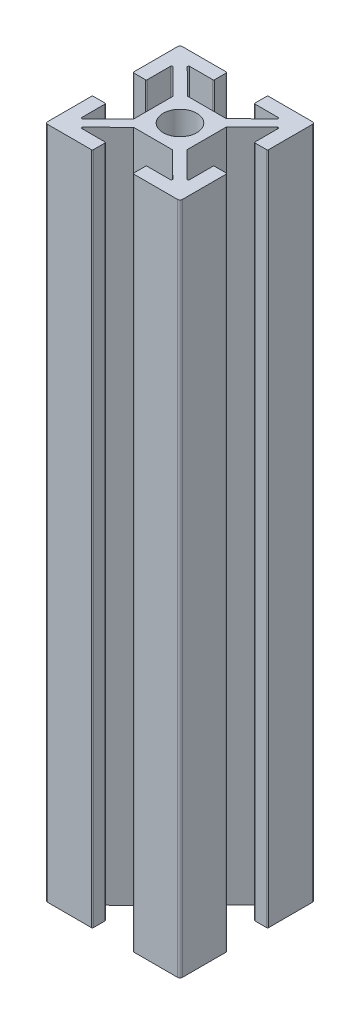
SolidWorks part; units mm, degrees
ref_plane "Front Plane" through (0, 0, 0) normal (0, 0, 1) x (1, 0, 0)
ref_plane "Top Plane" through (0, 0, 0) normal (0, 1, 0) x (1, 0, 0)
ref_plane "Right Plane" through (0, 0, 0) normal (1, 0, 0) x (0, 0, -1)
sketch "Sketch1" plane through (0, 0, 0) normal (0, 1, 0) x (1, 0, 0)
  line L0 (-5.3577, -5.6795) -> (-3.6577, -5.6795)
  line L1 (1.3423, 1.3205) -> (-5.1577, 1.3205)
  line L2 (-5.5077, -5.5295) -> (-5.5077, 0.9705)
  line L3 (7.3792, -4.6795) -> (1.6054, -4.6795)
  line L4 (0.5386, -11.6249) -> (0.5386, -5.7341)
  line L5 (-3.5077, -5.5295) -> (-3.5077, -2.0933)
  line L6 (-2.0758, -0.6795) -> (1.3423, -0.6795)
  line L7 (1.4923, -0.5295) -> (1.4923, 1.1705)
  line L8 (-3.5077, -0.6795) -> (0.5386, -4.6795) construction
  line L9 (-3.2523, -1.9866) -> (0.5386, -5.7341)
  line L10 (-2.1813, -0.9362) -> (1.6054, -4.6795)
  line L11 (12.4923, -0.6795) -> (8.446, -4.6795) construction
  line L12 (4.4923, -8.6795) -> (4.4923, 3.0091) construction
  line L13 (4.4923, -8.6795) -> (-10.4455, -8.6795) construction
  line L14 (11.1658, -0.9362) -> (7.3792, -4.6795)
  line L15 (12.2368, -1.9866) -> (8.446, -5.7341)
  line L16 (7.4923, -0.5295) -> (7.4923, 1.1705)
  line L17 (11.0604, -0.6795) -> (7.6423, -0.6795)
  line L18 (12.4923, -5.5295) -> (12.4923, -2.0933)
  line L19 (8.446, -11.6249) -> (8.446, -5.7341)
  line L20 (14.4923, -5.5295) -> (14.4923, 0.9705)
  line L21 (7.6423, 1.3205) -> (14.1423, 1.3205)
  line L22 (14.3423, -5.6795) -> (12.6423, -5.6795)
  line L23 (12.4923, -16.6795) -> (8.446, -12.6795) construction
  line L24 (-3.5077, -16.6795) -> (0.5386, -12.6795) construction
  line L25 (14.3423, -11.6795) -> (12.6423, -11.6795)
  line L26 (7.6423, -18.6795) -> (14.1423, -18.6795)
  line L27 (14.4923, -11.8295) -> (14.4923, -18.3295)
  line L28 (12.4923, -11.8295) -> (12.4923, -15.2657)
  line L29 (11.0604, -16.6795) -> (7.6423, -16.6795)
  line L30 (7.4923, -16.8295) -> (7.4923, -18.5295)
  line L31 (12.2368, -15.3723) -> (8.446, -11.6249)
  line L32 (11.1658, -16.4228) -> (7.3792, -12.6795)
  line L33 (-2.1813, -16.4228) -> (1.6054, -12.6795)
  line L34 (-3.2523, -15.3723) -> (0.5386, -11.6249)
  line L35 (1.4923, -16.8295) -> (1.4923, -18.5295)
  line L36 (-2.0758, -16.6795) -> (1.3423, -16.6795)
  line L37 (-3.5077, -11.8295) -> (-3.5077, -15.2657)
  line L38 (7.3792, -12.6795) -> (1.6054, -12.6795)
  line L39 (-5.5077, -11.8295) -> (-5.5077, -18.3295)
  line L40 (1.3423, -18.6795) -> (-5.1577, -18.6795)
  line L41 (-5.3577, -11.6795) -> (-3.6577, -11.6795)
  circle A0 centre (4.4923, -8.6795) radius 2.5
  arc A1 (-5.5077, 0.9705) -> (-5.1577, 1.3205) centre (-5.1577, 0.9705) cw
  arc A2 (-5.3577, -5.6795) -> (-5.5077, -5.5295) centre (-5.3577, -5.5295) cw
  arc A3 (-3.6577, -5.6795) -> (-3.5077, -5.5295) centre (-3.6577, -5.5295) ccw
  arc A4 (1.3423, 1.3205) -> (1.4923, 1.1705) centre (1.3423, 1.1705) cw
  arc A5 (1.3423, -0.6795) -> (1.4923, -0.5295) centre (1.3423, -0.5295) ccw
  arc A6 (-2.1813, -0.9362) -> (-2.0758, -0.6795) centre (-2.0758, -0.8295) cw
  arc A7 (-3.2523, -1.9866) -> (-3.5077, -2.0933) centre (-3.3577, -2.0933) ccw
  arc A8 (12.2368, -1.9866) -> (12.4923, -2.0933) centre (12.3423, -2.0933) cw
  arc A9 (11.1658, -0.9362) -> (11.0604, -0.6795) centre (11.0604, -0.8295) ccw
  arc A10 (7.6423, -0.6795) -> (7.4923, -0.5295) centre (7.6423, -0.5295) cw
  arc A11 (7.6423, 1.3205) -> (7.4923, 1.1705) centre (7.6423, 1.1705) ccw
  arc A12 (12.6423, -5.6795) -> (12.4923, -5.5295) centre (12.6423, -5.5295) cw
  arc A13 (14.3423, -5.6795) -> (14.4923, -5.5295) centre (14.3423, -5.5295) ccw
  arc A14 (14.4923, 0.9705) -> (14.1423, 1.3205) centre (14.1423, 0.9705) ccw
  arc A15 (14.4923, -18.3295) -> (14.1423, -18.6795) centre (14.1423, -18.3295) cw
  arc A16 (14.3423, -11.6795) -> (14.4923, -11.8295) centre (14.3423, -11.8295) cw
  arc A17 (12.6423, -11.6795) -> (12.4923, -11.8295) centre (12.6423, -11.8295) ccw
  arc A18 (7.6423, -18.6795) -> (7.4923, -18.5295) centre (7.6423, -18.5295) cw
  arc A19 (7.6423, -16.6795) -> (7.4923, -16.8295) centre (7.6423, -16.8295) ccw
  arc A20 (11.1658, -16.4228) -> (11.0604, -16.6795) centre (11.0604, -16.5295) cw
  arc A21 (12.2368, -15.3723) -> (12.4923, -15.2657) centre (12.3423, -15.2657) ccw
  arc A22 (-3.2523, -15.3723) -> (-3.5077, -15.2657) centre (-3.3577, -15.2657) cw
  arc A23 (-2.1813, -16.4228) -> (-2.0758, -16.6795) centre (-2.0758, -16.5295) ccw
  arc A24 (1.3423, -16.6795) -> (1.4923, -16.8295) centre (1.3423, -16.8295) cw
  arc A25 (1.3423, -18.6795) -> (1.4923, -18.5295) centre (1.3423, -18.5295) ccw
  arc A26 (-3.6577, -11.6795) -> (-3.5077, -11.8295) centre (-3.6577, -11.8295) cw
  arc A27 (-5.3577, -11.6795) -> (-5.5077, -11.8295) centre (-5.3577, -11.8295) ccw
  arc A28 (-5.5077, -18.3295) -> (-5.1577, -18.6795) centre (-5.1577, -18.3295) ccw
  point P27 (7.5849, -0.6795)
  point P28 (14.5849, -18.6795)
  point P47 (8.446, -8.6795)
  point P57 (4.4923, -4.6795)
  point P59 (7.5849, 1.3205)
  point P60 (12.5849, -5.6795)
  point P61 (14.5849, -5.6795)
  point P62 (14.5849, 1.3205)
  point P112 (0.5386, -8.6795)
  point P113 (14.5849, -11.6795)
  point P114 (12.5849, -11.6795)
  point P115 (7.5849, -18.6795)
  point P116 (4.4923, -12.6795)
  point P117 (1.4923, -16.6795)
  point P118 (1.4923, -18.6795)
  point P119 (-3.5077, -11.6795)
  point P120 (7.5849, -16.6795)
  point P121 (-5.5077, -11.6795)
  point P122 (-5.5077, -18.6795)
  dimension "D3" = 0.35
  dimension "D4" = 0.15
  dimension "D5" = 0.15
  dimension "D6" = 0.15
  dimension "D7" = 0.15
  dimension "D8" = 0.15
  dimension "D9" = 0.15
  dimension "D1" = 0.75
  dimension "D2" = 0.75
  dimension "D10" = 20
  dimension "D11" = 20
extrude "Boss-Extrude1" add sketch "Sketch1" along normal blind 100
